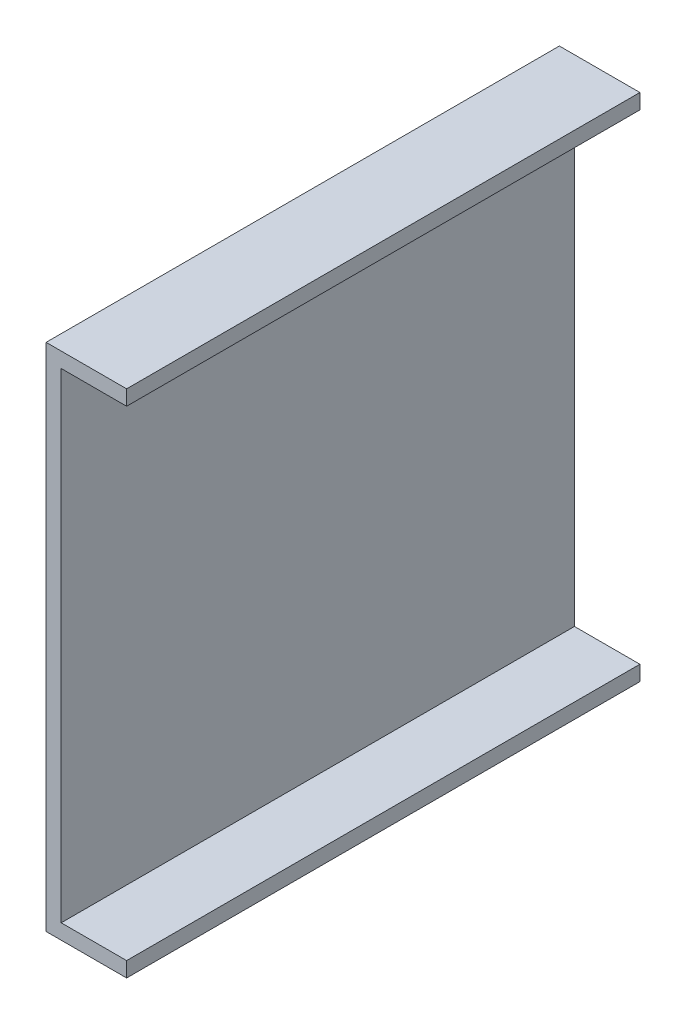
SolidWorks part; units mm, degrees
ref_plane "Front Plane" through (0, 0, 0) normal (0, 0, 1) x (1, 0, 0)
ref_plane "Top Plane" through (0, 0, 0) normal (0, 1, 0) x (1, 0, 0)
ref_plane "Right Plane" through (0, 0, 0) normal (1, 0, 0) x (0, 0, -1)
sketch "Sketch1" plane through (0, 0, 0) normal (0, 0, 1) x (1, 0, 0)
  line L0 (0, 0) -> (80, 0)
  line L1 (80, 0) -> (80, -15)
  line L2 (80, -15) -> (15, -15)
  line L3 (0, 0) -> (0, -507)
  line L4 (0, -507) -> (80, -507)
  line L5 (80, -507) -> (80, -492)
  line L6 (15, -15) -> (15, -492)
  line L7 (15, -492) -> (80, -492)
  dimension "D1" = 80
  dimension "D2" = 15
  dimension "D3" = 65
  dimension "D4" = 507
  dimension "D5" = 15
extrude "Boss-Extrude1" add sketch "Sketch1" along normal blind 510
sketch "Sketch2" plane through (0, 0, 0) normal (0, 1, 0) x (1, 0, 0)
  point P0 (38.4796, -35.9991)
